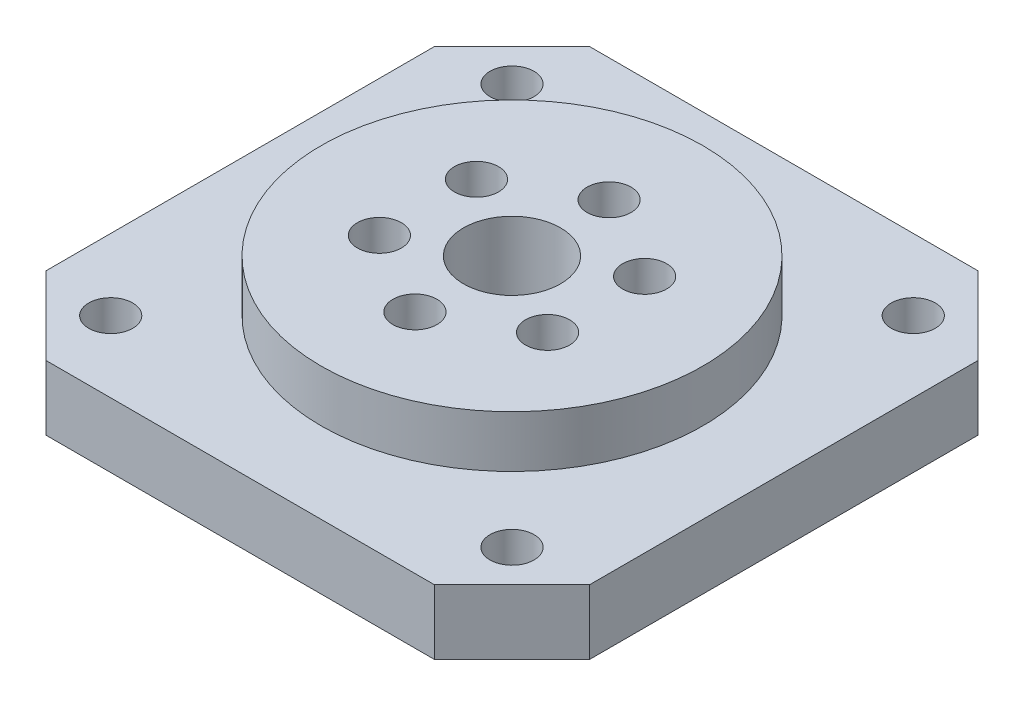
SolidWorks part; units mm, degrees
ref_plane "Ön Düzlem" through (0, 0, 0) normal (0, 0, 1) x (1, 0, 0)
ref_plane "Üst Düzlem" through (0, 0, 0) normal (0, 1, 0) x (1, 0, 0)
ref_plane "Sağ Düzlem" through (0, 0, 0) normal (1, 0, 0) x (0, 0, -1)
sketch "Sketch1" plane through (0, 0, 0) normal (0, 1, 0) x (1, 0, 0)
  line L0 (-21, 15) -> (-21, -15)
  line L5 (-15, 21) -> (15, 21)
  line L6 (21, 15) -> (21, -15)
  line L7 (-15, -21) -> (15, -21)
  line L8 (-21, 15) -> (-15, 21)
  line L9 (15, 21) -> (21, 15)
  line L10 (21, -15) -> (15, -21)
  line L11 (-15, -21) -> (-21, -15)
  point P2 (-21, 0)
  point P10 (0, 21)
  point P11 (21, 0)
  point P13 (0, -21)
  dimension "D1" = 21
  dimension "D2" = 30
  dimension "D3" = 21
  dimension "D4" = 21
  dimension "D5" = 21
extrude "Boss-Extrude1" add sketch "Sketch1" along normal blind 5
sketch "Sketch5" plane through (0, 5, 0) normal (0, 1, 0) x (1, 0, 0)
  line L1 (-15.5, -15.5) -> (15.5, -15.5) construction
  line L2 (-15.5, -15.5) -> (-15.5, 15.5) construction
  line L3 (-15.5, 15.5) -> (15.5, 15.5) construction
  line L4 (15.5, -15.5) -> (15.5, 15.5) construction
  line L5 (-15.5, -15.5) -> (15.5, 15.5) construction
  line L6 (-15.5, 15.5) -> (15.5, -15.5) construction
  point P9 (-15.5, 15.5)
  point P12 (-15.5, -15.5)
  point P15 (15.5, -15.5)
  point P18 (15.5, 15.5)
  dimension "D1" = 31
hole_wizard "M3 Clearance Hole1" positions "Sketch5" profile "Sketch6" hole size "M3" standard "ANSI Metric" end condition through all
sketch "Sketch6" plane through (15.5, 5, -15.5) normal (1, 0, 0) x (0, 0, 1)
  line L0 (0, 0) -> (0, 5)
  line L1 (0, 5) -> (1.7, 5)
  line L2 (1.7, 5) -> (1.7, 0)
  line L5 (1.7, 0) -> (0, 0)
  line L11 (0, -6.35) -> (0, 107.95) construction
  dimension "Thru Hole Dia." = 3.4
  dimension "Thru Hole Depth" = 5
sketch "Sketch2" plane through (0, 5, 0) normal (0, 1, 0) x (1, 0, 0)
  circle A0 centre (0, 0) radius 14.75
  dimension "D1" = 29.5
extrude "Boss-Extrude2" add sketch "Sketch2" along normal blind 4 contours A0
sketch "Sketch4" plane through (0, 0, 0) normal (0, -1, 0) x (-1, 0, 0)
  circle A0 centre (0, 0) radius 12
  dimension "D1" = 24
extrude "Cut-Extrude1" cut sketch "Sketch4" against normal blind 3.5
sketch "Sketch3" plane through (0, 9, 0) normal (0, 1, 0) x (1, 0, 0)
  circle A0 centre (0, 0) radius 7.5 construction
  circle A1 centre (0, 7.5) radius 1.7
  circle A2 centre (0.0005, 0.0009) radius 7.5 construction
  circle A3 centre (6.4957, 3.7509) radius 1.7
  circle A4 centre (0.0015, 0.0009) radius 7.5 construction
  circle A5 centre (6.4967, -3.7491) radius 1.7
  circle A6 centre (0.002, 0) radius 7.5 construction
  circle A7 centre (0.002, -7.5) radius 1.7
  circle A8 centre (0.0015, -0.0009) radius 7.5 construction
  circle A9 centre (-6.4937, -3.7509) radius 1.7
  circle A10 centre (0.0005, -0.0009) radius 7.5 construction
  circle A11 centre (-6.4947, 3.7491) radius 1.7
  point P27 (0.001, 0)
  dimension "D1" = 15
  dimension "D2" = 3.4
  dimension "D3" = 6
sketch "Sketch7" plane through (0, 3.5, 0) normal (0, -1, 0) x (1, 0, 0)
  line L0 (3.6452, 2.1046) -> (6.4952, 0.4591)
  line L1 (0, 4.2091) -> (2.85, 5.8546)
  line L2 (2.85, 5.8546) -> (2.85, 9.1454)
  line L3 (2.85, 9.1454) -> (0, 10.7909)
  line L4 (0, 10.7909) -> (-2.85, 9.1454)
  line L5 (-2.85, 9.1454) -> (-2.85, 5.8546)
  line L6 (-2.85, 5.8546) -> (0, 4.2091)
  line L7 (6.4952, 0.4591) -> (9.3452, 2.1046)
  line L8 (9.3452, 2.1046) -> (9.3452, 5.3954)
  line L9 (9.3452, 5.3954) -> (6.4952, 7.0409)
  line L10 (6.4952, 7.0409) -> (3.6452, 5.3954)
  line L11 (3.6452, 5.3954) -> (3.6452, 2.1046)
  line L12 (3.6452, -2.1046) -> (3.6452, -5.3954)
  line L13 (3.6452, -5.3954) -> (6.4952, -7.0409)
  line L14 (6.4952, -7.0409) -> (9.3452, -5.3954)
  line L15 (9.3452, -5.3954) -> (9.3452, -2.1046)
  line L16 (9.3452, -2.1046) -> (6.4952, -0.4591)
  line L17 (6.4952, -0.4591) -> (3.6452, -2.1046)
  line L18 (0, -4.2091) -> (-2.85, -5.8546)
  line L19 (-2.85, -5.8546) -> (-2.85, -9.1454)
  line L20 (-2.85, -9.1454) -> (0, -10.7909)
  line L21 (0, -10.7909) -> (2.85, -9.1454)
  line L22 (2.85, -9.1454) -> (2.85, -5.8546)
  line L23 (2.85, -5.8546) -> (0, -4.2091)
  line L24 (-3.6452, -2.1046) -> (-6.4952, -0.4591)
  line L25 (-6.4952, -0.4591) -> (-9.3452, -2.1046)
  line L26 (-9.3452, -2.1046) -> (-9.3452, -5.3954)
  line L27 (-9.3452, -5.3954) -> (-6.4952, -7.0409)
  line L28 (-6.4952, -7.0409) -> (-3.6452, -5.3954)
  line L29 (-3.6452, -5.3954) -> (-3.6452, -2.1046)
  line L30 (-3.6452, 2.1046) -> (-3.6452, 5.3954)
  line L31 (-3.6452, 5.3954) -> (-6.4952, 7.0409)
  line L32 (-6.4952, 7.0409) -> (-9.3452, 5.3954)
  line L33 (-9.3452, 5.3954) -> (-9.3452, 2.1046)
  line L34 (-9.3452, 2.1046) -> (-6.4952, 0.4591)
  line L35 (-6.4952, 0.4591) -> (-3.6452, 2.1046)
  circle A0 centre (0, 7.5) radius 2.85 construction
  point P41 (0, 0)
  dimension "D1" = 5.7
  dimension "D2" = 7.5
  dimension "D3" = 6
extrude "Cut-Extrude2" cut sketch "Sketch7" against normal blind 2.5
sketch "Sketch8" plane through (0, 3.5, 0) normal (0, -1, 0) x (1, 0, 0)
  circle A0 centre (0, 0) radius 3.75
  dimension "D1" = 7.5
extrude "Cut-Extrude3" cut sketch "Sketch8" against normal through all
extrude "Cut-Extrude4" cut sketch "Sketch3" against normal through all
